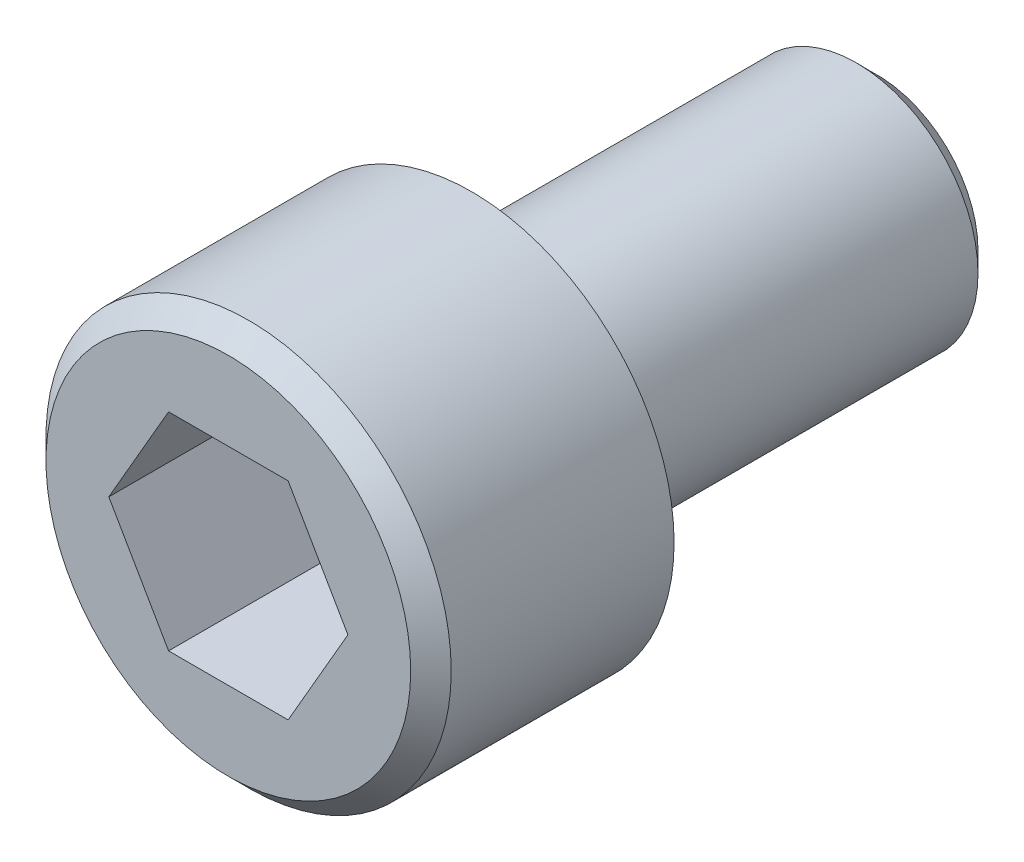
SolidWorks part; units mm, degrees
ref_plane "Alzado" through (0, 0, 0) normal (0, 0, 1) x (1, 0, 0)
ref_plane "Planta" through (0, 0, 0) normal (0, 1, 0) x (1, 0, 0)
ref_plane "Vista lateral" through (0, 0, 0) normal (1, 0, 0) x (0, 0, -1)
sketch "Croquis1" plane through (0, 0, 0) normal (0, 0, 1) x (1, 0, 0)
  circle A0 centre (0, 0) radius 5
  dimension "D1" = 10
extrude "Saliente-Extruir1" add sketch "Croquis1" along normal blind 6
sketch "Croquis2" plane through (0, 0, 0) normal (0, 0, -1) x (-1, 0, 0)
  circle A0 centre (0, 0) radius 3
  dimension "D1" = 6
extrude "Saliente-Extruir2" add sketch "Croquis2" along normal blind 10
chamfer "Chaflán1" distance 0.5 angle 45 2 edges at (5, 0, 6) (-3, 0, -10)
sketch "Croquis3" plane through (0, 0, 6) normal (0, 0, 1) x (1, 0, 0)
  line L1 (2.95, 0) -> (1.475, 2.5548)
  line L2 (1.475, 2.5548) -> (-1.475, 2.5548)
  line L3 (-1.475, 2.5548) -> (-2.95, 0)
  line L4 (-2.95, 0) -> (-1.475, -2.5548)
  line L5 (-1.475, -2.5548) -> (1.475, -2.5548)
  line L6 (1.475, -2.5548) -> (2.95, 0)
  circle A0 centre (0, 0) radius 2.5548 construction
  dimension "D1" = 5.9
extrude "Cortar-Extruir1" cut sketch "Croquis3" against normal blind 4
